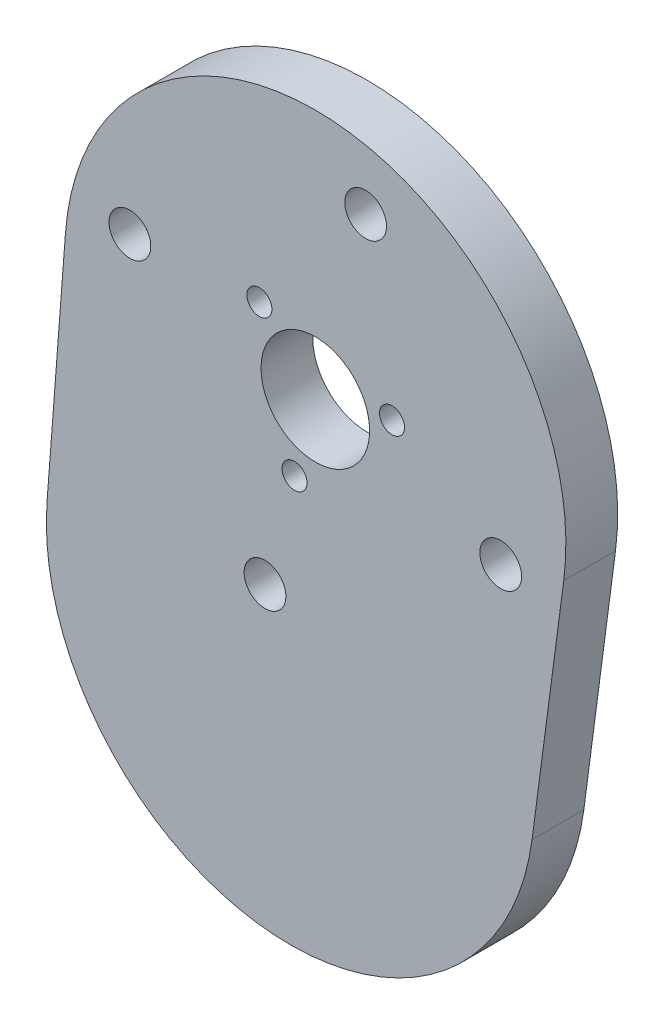
SolidWorks part; units mm, degrees
ref_plane "Front Plane" through (0, 0, 0) normal (0, 0, 1) x (1, 0, 0)
ref_plane "Top Plane" through (0, 0, 0) normal (0, 1, 0) x (1, 0, 0)
ref_plane "Right Plane" through (0, 0, 0) normal (1, 0, 0) x (0, 0, -1)
sketch "Sketch1" plane through (0, 0, 0) normal (0, 0, 1) x (1, 0, 0)
  line L1 (25.949, -32.6651) -> (29.7421, -3.9254)
  line L2 (-29.9133, 2.2791) -> (-32.1156, -26.6261)
  circle A0 centre (22.197, -6.0244) radius 2.5
  circle A1 centre (-22.197, 6.0244) radius 2.5
  circle A2 centre (6.0244, 22.197) radius 2.5
  circle A3 centre (-6.0244, -22.197) radius 2.5
  circle A4 centre (0, 0) radius 6.5
  arc A5 (-32.1156, -26.6261) -> (25.949, -32.6651) centre (-3, -28.8444) ccw
  arc A6 (29.7421, -3.9254) -> (-29.9133, 2.2791) centre (0, 0) ccw
  circle A7 centre (0, 0) radius 23 construction
  dimension "D1" = 13
  dimension "D2" = 46
  dimension "D3" = 5
  dimension "D5" = 30
  dimension "D6" = 29.2
  dimension "D4" = 29
  dimension "D7" = 3
extrude "Boss-Extrude1" add sketch "Sketch1" along normal blind 6.2 contours L1 A6 L2 A5 A0 A1 A2 A3 A4
sketch "Sketch2" plane through (0, 0, 6.2) normal (0, 0, 1) x (1, 0, 0)
  circle A0 centre (9.1842, 2.4292) radius 1.5 construction
  circle A1 centre (-6.6958, 6.7391) radius 1.5 construction
  circle A2 centre (-2.4883, -9.1683) radius 1.5 construction
  circle A3 centre (9.1842, 2.4292) radius 1.5
  circle A4 centre (-6.6958, 6.7391) radius 1.5
  circle A5 centre (-2.4883, -9.1683) radius 1.5
extrude "Cut-Extrude1" cut sketch "Sketch2" against normal up to next
